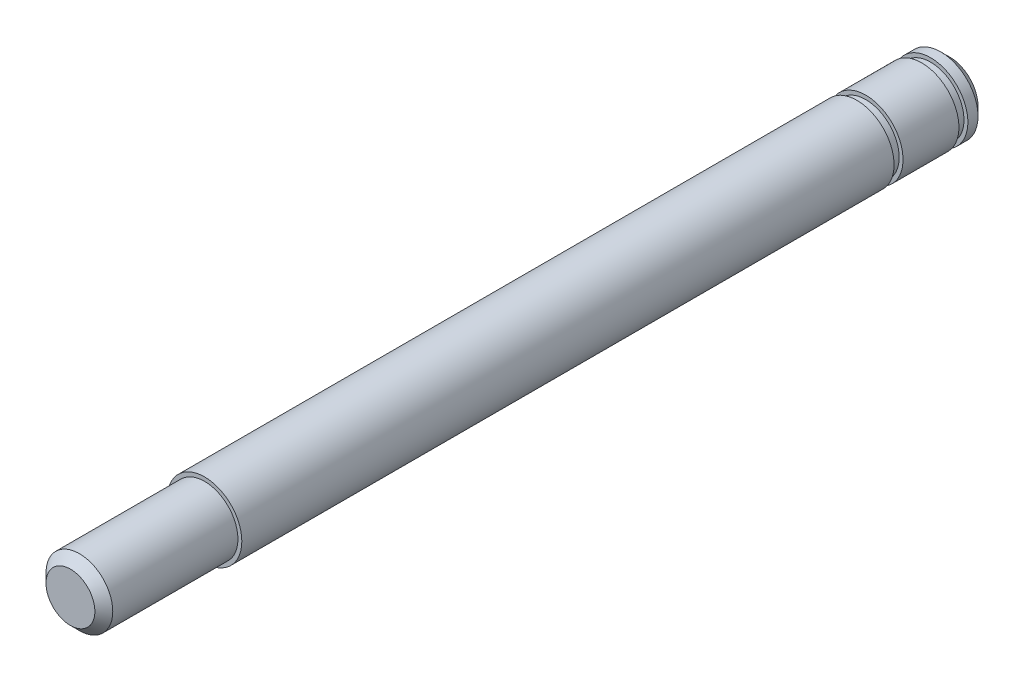
SolidWorks part; units mm, degrees
material "Alloy Steel"
ref_plane "Front Plane" through (0, 0, 0) normal (0, 0, 1) x (1, 0, 0)
ref_plane "Top Plane" through (0, 0, 0) normal (0, 1, 0) x (1, 0, 0)
ref_plane "Right Plane" through (0, 0, 0) normal (1, 0, 0) x (0, 0, -1)
sketch "Sketch1" plane through (0, 0, 0) normal (0, 0, 1) x (1, 0, 0)
  circle A0 centre (0, 0) radius 1.5875
  dimension "D1" = 3.175
extrude "Boss-Extrude1" add sketch "Sketch1" along normal mid plane 31.75
sketch "Sketch2" plane through (0, 0, 15.875) normal (0, 0, 1) x (1, 0, 0)
  circle A0 centre (0, 0) radius 1.4224
  dimension "D1" = 2.8448
extrude "Boss-Extrude2" add sketch "Sketch2" along normal blind 5.715
ref_plane "Plane1" through (0, 0, -15.0622) normal (0, 0, -1) x (-1, 0, 0)
sketch "Sketch3" plane through (0, 0, -15.0622) normal (0, 0, -1) x (-1, 0, 0)
  circle A0 centre (0, 0) radius 1.5875 construction
  circle A1 centre (0, 0) radius 1.4224 construction
  circle A2 centre (0, 0) radius 1.5875
  circle A3 centre (0, 0) radius 1.4224
extrude "Cut-Extrude1" cut sketch "Sketch3" against normal blind 0.381
ref_plane "Plane2" through (0, 0, -12.3) normal (0, 0, -1) x (-1, 0, 0)
sketch "Sketch4" plane through (0, 0, -12.3) normal (0, 0, -1) x (-1, 0, 0)
  circle A0 centre (0, 0) radius 1.4224 construction
  circle A1 centre (0, 0) radius 1.5875 construction
  circle A2 centre (0, 0) radius 1.4224
  circle A3 centre (0, 0) radius 1.5875
extrude "Cut-Extrude2" cut sketch "Sketch4" against normal blind 0.381
chamfer "Chamfer1" distance 0.381 angle 45 2 edges at (1.4224, 0, 21.59) (1.5875, 0, -15.875)
cosmetic thread "Cosmetic Thread1" parameters "D2"=2.0879
